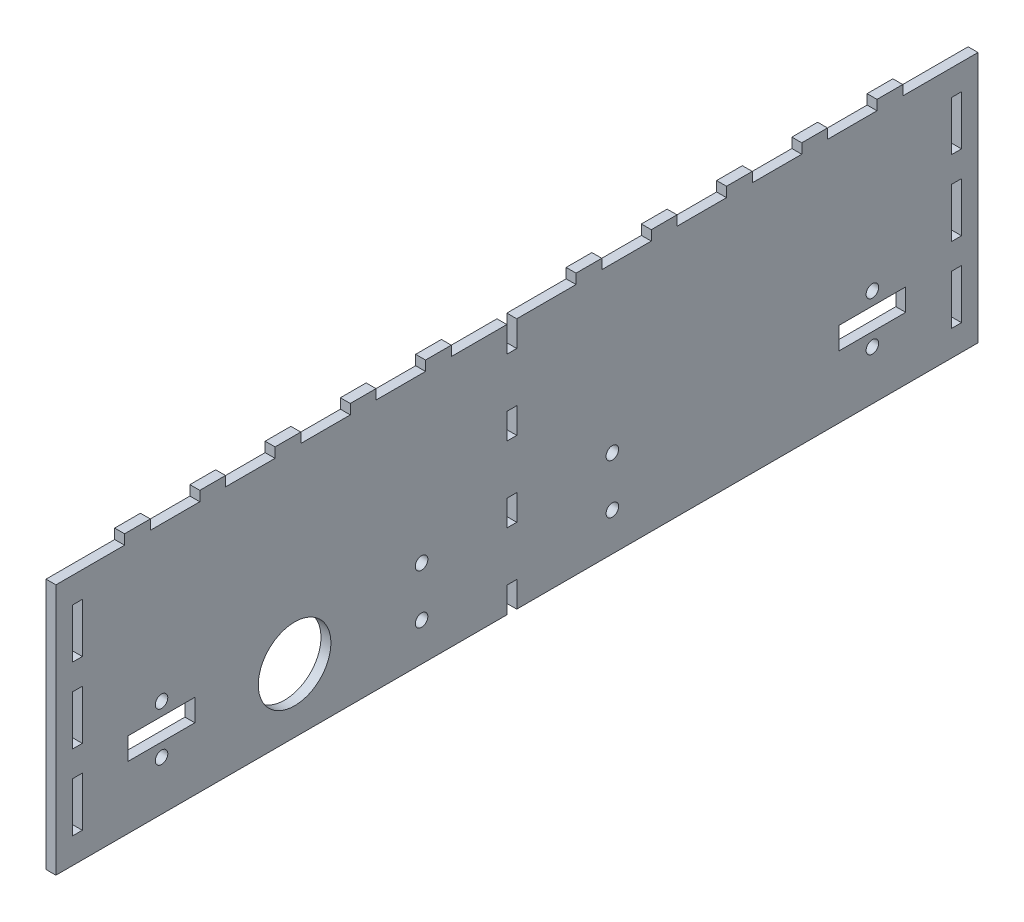
SolidWorks part; units mm, degrees
material "ENPH 253 Hardboard"
ref_plane "Front Plane" through (0, 0, 0) normal (0, 0, 1) x (1, 0, 0)
ref_plane "Top Plane" through (0, 0, 0) normal (0, 1, 0) x (1, 0, 0)
ref_plane "Right Plane" through (0, 0, 0) normal (1, 0, 0) x (0, 0, -1)
sketch "Sketch1" plane through (0, 0, 0) normal (1, 0, 0) x (0, 0, -1)
  line L1 (-139.7, 38.1) -> (139.7, 38.1)
  line L2 (-139.7, 38.1) -> (-139.7, -38.1)
  line L3 (-139.7, -38.1) -> (139.7, -38.1)
  line L4 (139.7, 38.1) -> (139.7, -38.1)
  line L5 (-139.7, 38.1) -> (139.7, -38.1) construction
  line L6 (-139.7, -38.1) -> (139.7, 38.1) construction
  point P0 (0, 0)
  dimension "D1" = 279.4
  dimension "D2" = 76.2
extrude "Boss-Extrude1" add sketch "Sketch1" against normal blind 3 contours L2 L3 L4 L1
sketch "Sketch3" plane through (-3, 0, 0) normal (-1, 0, 0) x (0, 0, 1)
  line L0 (-139.7, 38.1) -> (-139.7, -38.1) construction
  line L1 (139.7, 38.1) -> (139.7, -38.1) construction
  line L2 (139.7, 38.1) -> (-139.7, 38.1) construction
  line L3 (134.7, 30.3) -> (131.7, 30.3)
  line L4 (134.7, 30.3) -> (134.7, 15.3)
  line L5 (134.7, 15.3) -> (131.7, 15.3)
  line L6 (131.7, 30.3) -> (131.7, 15.3)
  line L7 (139.7, 38.1) -> (139.7, -38.1) construction
  circle A0 centre (69.85, 0) radius 50.8 construction
  circle A1 centre (-69.85, 0) radius 50.8 construction
  dimension "D1" = 101.6
  dimension "D2" = 101.6
  dimension "D3" = 69.85
  dimension "D4" = 69.85
  dimension "D5" = 15
  dimension "D6" = 7.8
  dimension "D7" = 5
  dimension "D8" = 3
extrude "Cut-Extrude1" cut sketch "Sketch3" against normal through all
pattern_linear "LPattern1" count 3 spacing 22.8 along (0, -1, 0) of "Cut-Extrude1"
mirror "Mirror1" about plane through (0, 0, 0) normal (0, 0, 1) of "LPattern1", "Cut-Extrude1"
sketch "Sketch6" plane through (-3, 0, 0) normal (-1, 0, 0) x (0, 0, 1)
  line L0 (139.7, 38.1) -> (-139.7, 38.1) construction
  line L1 (0.06, 38.1) -> (3.06, 38.1)
  line L2 (0.06, 38.1) -> (0.06, 30.3)
  line L3 (0.06, 30.3) -> (3.06, 30.3)
  line L4 (3.06, 38.1) -> (3.06, 30.3)
  dimension "D1" = 136.64
  dimension "D2" = 3
  dimension "D3" = 7.8
extrude "Cut-Extrude2" cut sketch "Sketch6" against normal through all
pattern_linear "LPattern2" count 4 spacing 22.8 along (0, -1, 0) of "Cut-Extrude2"
sketch "Sketch8" plane through (0, 38.1, 0) normal (0, 1, 0) x (1, 0, 0)
  line L0 (0, -139.7) -> (0, -3.06) construction
  line L1 (0, 116.9) -> (-3, 116.9)
  line L2 (0, 116.9) -> (0, 109.1)
  line L3 (0, 109.1) -> (-3, 109.1)
  line L4 (-3, 116.9) -> (-3, 109.1)
  line L5 (-3, -139.7) -> (-3, -3.06) construction
  line L7 (-3, 139.7) -> (0, 139.7) construction
  dimension "D1" = 22.8
  dimension "D2" = 7.8
extrude "Boss-Extrude2" add sketch "Sketch8" along normal blind 3
pattern_linear "LPattern4" count 11 spacing 22.8 along (0, 0, 1) skipping (5, 0) of "Boss-Extrude2"
sketch "Sketch9" plane through (-3, 0, 0) normal (-1, 0, 0) x (0, 0, 1)
  line L0 (139.7, -38.1) -> (3.06, -38.1) construction
  line L1 (3.06, -15.3) -> (3.06, -7.5) construction
  circle A0 centre (67.38, -18.8) radius 11
  dimension "D1" = 22
  dimension "D2" = 19.3
  dimension "D3" = 64.32
extrude "Cut-Extrude3" cut sketch "Sketch9" against normal through all contours A0
hole_wizard "#6 Clearance Hole1" positions "Sketch10" profile "Sketch11" hole size "#6" standard "ANSI Inch" end condition up to next
sketch "Sketch10" plane through (0, 0, 0) normal (1, 0, 0) x (0, 0, -1)
  circle A0 centre (28.9, -26.55) radius 1.8987 construction
  point P0 (28.9, -26.55)
  point P2 (28.9, -11.55)
  point P5 (-28.9, -11.55)
  point P8 (-28.9, -26.55)
sketch "Sketch11" plane through (0, -26.55, -28.9) normal (0, 1, 0) x (0, 0, -1)
  line L0 (0, 0) -> (0, 3)
  line L1 (0, 3) -> (1.8986, 3)
  line L2 (1.8986, 3) -> (1.8986, 0)
  line L5 (1.8986, 0) -> (0, 0)
  line L11 (0, -6.35) -> (0, 107.95) construction
  dimension "Thru Hole Dia." = 3.7973
  dimension "Thru Hole Depth" = 3
sketch "Sketch12" plane through (-3, 0, 0) normal (-1, 0, 0) x (0, 0, 1)
  line L0 (-134.7, -30.3) -> (-134.7, -15.3) construction
  line L1 (-117.7, -19.05) -> (-97.7, -19.05) construction
  line L2 (-117.7, -19.05) -> (-117.7, -12.55) construction
  line L3 (-117.7, -12.55) -> (-97.7, -12.55) construction
  line L4 (-97.7, -19.05) -> (-97.7, -12.55) construction
  line L5 (0.06, -38.1) -> (-139.7, -38.1) construction
  line L6 (-117.8, -19.15) -> (-97.6, -19.15)
  line L7 (-97.6, -19.15) -> (-97.6, -12.45)
  line L8 (-117.8, -12.45) -> (-97.6, -12.45)
  line L9 (-117.8, -19.15) -> (-117.8, -12.45)
  line L10 (-139.7, 8.007) -> (139.7, 8.007) construction
  line L11 (-139.7, 38.1) -> (-139.7, -38.1) construction
  line L12 (139.7, 38.1) -> (139.7, -38.1) construction
  line L13 (0, 8.007) -> (0, -38.1) construction
  line L14 (97.7, -19.05) -> (97.7, -12.55) construction
  line L15 (117.7, -12.55) -> (97.7, -12.55) construction
  line L16 (117.7, -19.05) -> (117.7, -12.55) construction
  line L17 (117.7, -19.05) -> (97.7, -19.05) construction
  line L18 (117.8, -19.15) -> (117.8, -12.45)
  line L19 (117.8, -12.45) -> (97.6, -12.45)
  line L20 (97.6, -19.15) -> (97.6, -12.45)
  line L21 (117.8, -19.15) -> (97.6, -19.15)
  point P21 (-107.7, -8.45)
  point P22 (-107.7, -23.15)
  point P32 (-107.7, -12.45)
  point P34 (107.7, -23.15)
  point P35 (107.7, -8.45)
  dimension "D1" = 17
  dimension "D2" = 19.05
  dimension "D3" = 6.5
  dimension "D4" = 20
  dimension "D6" = 4
  dimension "D7" = 4
  dimension "D5" = 0.1
extrude "Cut-Extrude4" cut sketch "Sketch12" against normal up to next
hole_wizard "#6 Clearance Hole2" positions "Sketch13" profile "Sketch14" hole size "#6" standard "ANSI Inch" end condition through all
sketch "Sketch13" plane through (-3, 0, 0) normal (-1, 0, 0) x (0, 0, 1)
  line L0 (-117.8, -15.8) -> (117.8, -15.8) construction
  line L1 (-117.8, -12.45) -> (-117.8, -19.15) construction
  line L2 (117.8, -19.15) -> (117.8, -12.45) construction
  line L4 (0, -15.8) -> (0, -97.249) construction
  line L7 (-117.8, -19.15) -> (-97.6, -19.15) construction
  line L8 (-117.8, -19.15) -> (-97.6, -19.15) construction
  point P0 (-107.7, -23.15)
  point P36 (-107.7, -19.15)
  point P37 (-107.7, -8.45)
  point P39 (107.7, -23.15)
  point P40 (107.7, -8.45)
  dimension "D1" = 4
sketch "Sketch14" plane through (-3, -23.15, -107.7) normal (0, 1, 0) x (0, 0, 1)
  line L0 (0, 0) -> (0, 3)
  line L1 (0, 3) -> (1.8986, 3)
  line L2 (1.8986, 3) -> (1.8986, 0)
  line L5 (1.8986, 0) -> (0, 0)
  line L11 (0, -6.35) -> (0, 107.95) construction
  dimension "Thru Hole Dia." = 3.7973
  dimension "Thru Hole Depth" = 3
equation "\"D4@Sketch3\"=\"D3@Sketch3\""
